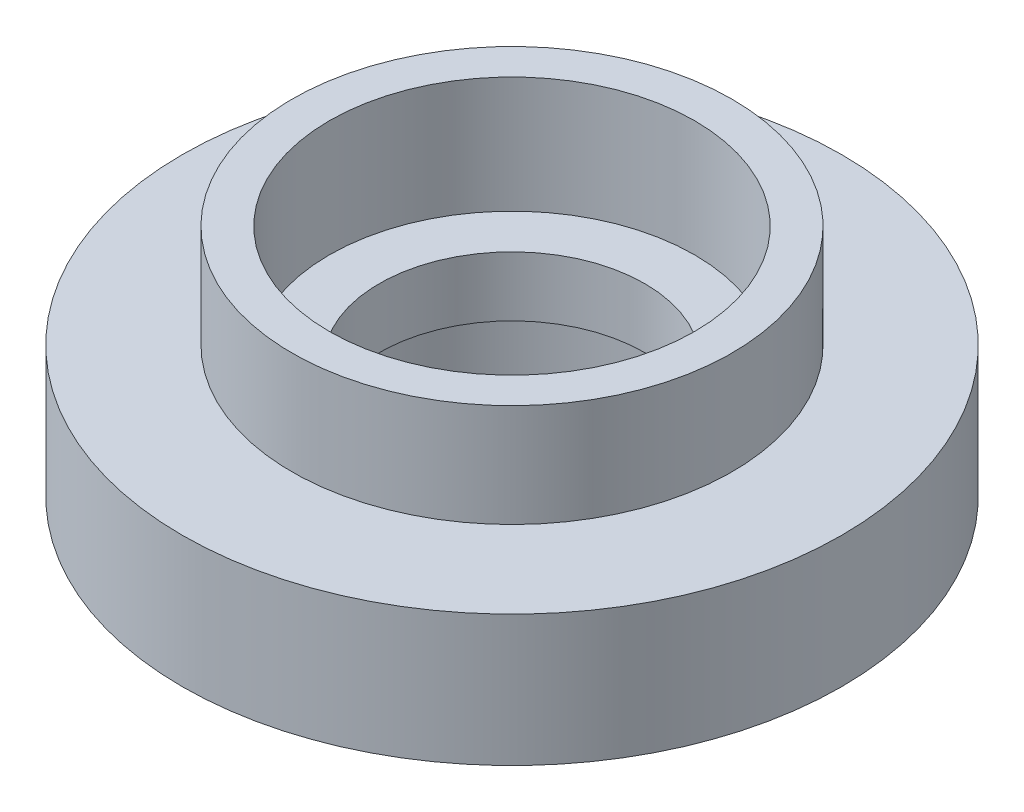
SolidWorks part; units mm, degrees
material "Nailon 6/10"
ref_plane "Alzado" through (0, 0, 0) normal (0, 0, 1) x (1, 0, 0)
ref_plane "Planta" through (0, 0, 0) normal (0, 1, 0) x (1, 0, 0)
ref_plane "Vista lateral" through (0, 0, 0) normal (1, 0, 0) x (0, 0, -1)
sketch "Croquis1" plane through (0, 0, 0) normal (0, 1, 0) x (1, 0, 0)
  circle A0 centre (0, 0) radius 19.86
  dimension "D1" = 39.72
extrude "Saliente-Extruir1" add sketch "Croquis1" along normal blind 7.9
sketch "Croquis2" plane through (0, 7.9, 0) normal (0, 1, 0) x (1, 0, 0)
  circle A0 centre (0, 0) radius 8
  dimension "D1" = 16
extrude "Cortar-Extruir1" cut sketch "Croquis2" against normal blind 7.9
sketch "Croquis3" plane through (0, 7.9, 0) normal (0, 1, 0) x (1, 0, 0)
  circle A0 centre (0, 0) radius 13.25
  circle A1 centre (0, 0) radius 11
  dimension "D1" = 26.5
  dimension "D2" = 22
extrude "Saliente-Extruir2" add sketch "Croquis3" along normal blind 6.2
sketch "Croquis4" plane through (0, 0, 0) normal (0, -1, 0) x (1, 0, 0)
  circle A0 centre (0, 0) radius 11
  circle A1 centre (0, 0) radius 13.25
  dimension "D1" = 22
  dimension "D2" = 26.5
extrude "Saliente-Extruir3" add sketch "Croquis4" along normal blind 3.5
sketch "Croquis5" plane through (0, -3.5, 0) normal (0, -1, 0) x (1, 0, 0)
  circle A0 centre (0, 0) radius 11
extrude "Cortar-Extruir2" cut sketch "Croquis5" against normal blind 7
sketch "Croquis6" plane through (0, 14.1, 0) normal (0, 1, 0) x (1, 0, 0)
  circle A0 centre (0, 0) radius 11
extrude "Cortar-Extruir3" cut sketch "Croquis6" against normal blind 7
